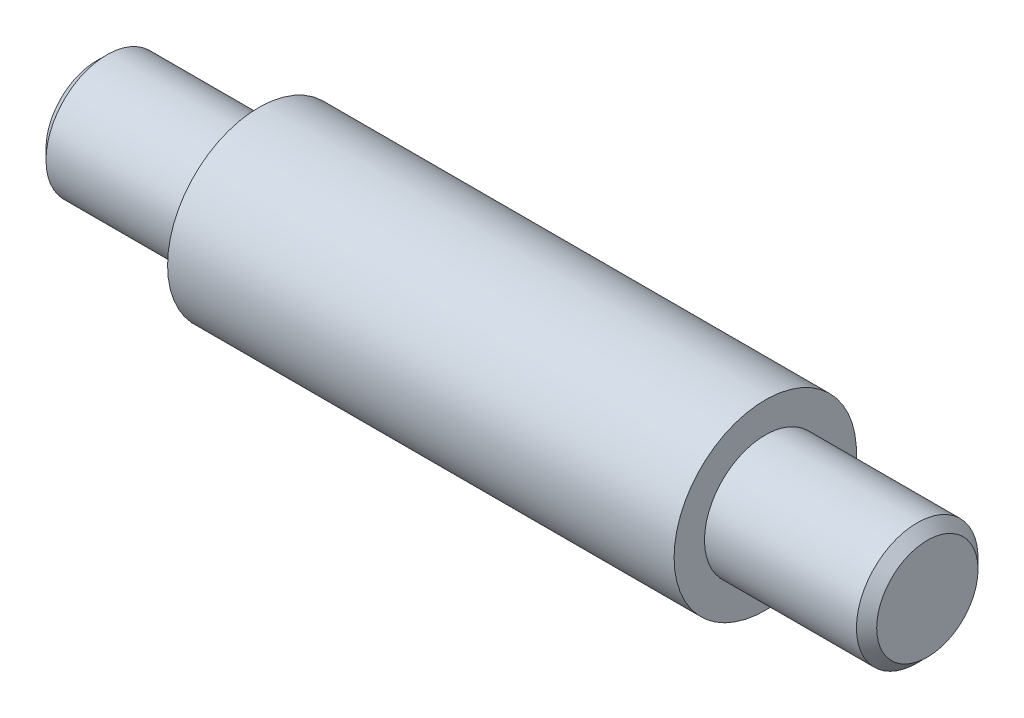
SolidWorks part; units mm, degrees
ref_plane "Front Plane" through (0, 0, 0) normal (0, 0, 1) x (1, 0, 0)
ref_plane "Top Plane" through (0, 0, 0) normal (0, 1, 0) x (1, 0, 0)
ref_plane "Right Plane" through (0, 0, 0) normal (1, 0, 0) x (0, 0, -1)
sketch "Sketch1" plane through (0, 0, 0) normal (0, 0, 1) x (1, 0, 0)
  line L0 (0, 0) -> (50000, 0) construction
  line L1 (40, 6) -> (41, 5)
  line L2 (-25, 9) -> (25, 9)
  line L3 (25, 9) -> (25, 6)
  line L4 (25, 6) -> (40, 6)
  line L5 (41, 5) -> (41, 0)
  line L6 (-41, 5) -> (-41, 0)
  line L7 (-25, 6) -> (-40, 6)
  line L8 (-25, 9) -> (-25, 6)
  line L9 (-40, 6) -> (-41, 5)
  line L10 (41, 0) -> (-41, 0)
  point P8 (41, 6)
  point P9 (-41, 6)
  dimension "D3" = 3
  dimension "D4" = 16
revolve "Revolve1" add sketch "Sketch1" angle 360 about L0
